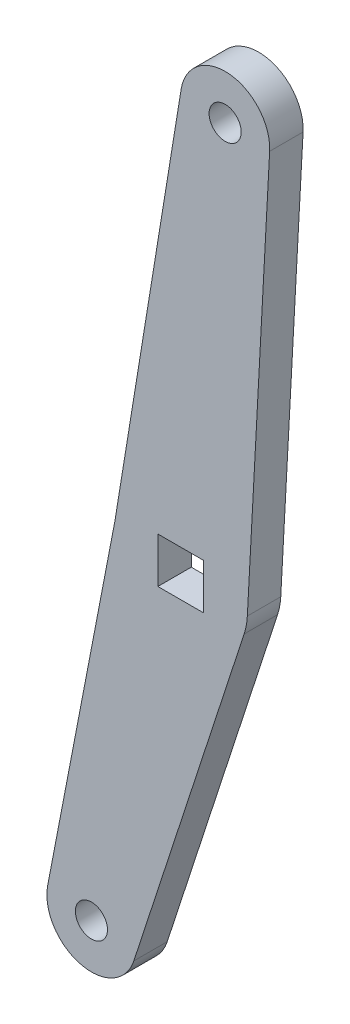
SolidWorks part; units mm, degrees
ref_plane "Front Plane" through (0, 0, 0) normal (0, 0, 1) x (1, 0, 0)
ref_plane "Top Plane" through (0, 0, 0) normal (0, 1, 0) x (1, 0, 0)
ref_plane "Right Plane" through (0, 0, 0) normal (1, 0, 0) x (0, 0, -1)
sketch "Sketch1" plane through (0, 0, 0) normal (0, 0, 1) x (1, 0, 0)
  line L0 (-6.2355, 1.2002) -> (3.3306, 50.8999)
  line L1 (0, 0) -> (29.7258, 0) construction
  line L2 (6.0371, -1.9687) -> (21.7557, 46.2339)
  line L3 (3.3626, 51.0802) -> (12.7824, 108.9699)
  line L4 (22.2112, 48.6737) -> (25.3908, 107.6079)
  line L7 (21.7557, 46.2339) -> (22.2112, 48.6737) construction
  line L8 (-2.905, 52.1001) -> (22.0632, 47.4389) construction
  line L10 (9.4615, 45.9484) -> (15.9385, 45.9484)
  line L11 (9.4615, 45.9484) -> (9.4615, 52.4254)
  line L12 (9.4615, 52.4254) -> (15.9385, 52.4254)
  line L13 (15.9385, 45.9484) -> (15.9385, 52.4254)
  line L14 (9.4615, 45.9484) -> (15.9385, 52.4254) construction
  line L15 (9.4615, 52.4254) -> (15.9385, 45.9484) construction
  circle A0 centre (0, 0) radius 2.286
  arc A1 (-6.2355, 1.2002) -> (6.0371, -1.9687) centre (0, 0) ccw
  circle A2 centre (19.05, 107.95) radius 2.286
  arc A4 (25.3908, 107.6079) -> (12.7824, 108.9699) centre (19.05, 107.95) ccw
  arc A8 (21.7557, 46.2339) -> (22.2112, 48.6737) centre (12.7, 49.1869) ccw
  arc A9 (3.3306, 50.8999) -> (3.3626, 51.0802) centre (-2.905, 52.1001) ccw
  circle A11 centre (19.05, 107.95) radius 2.286 construction
  arc A12 (12.7, 47.9369) -> (12.7, 50.4369) centre (12.7, 49.1869) ccw construction
  point P17 (3.3472, 50.99)
  point P21 (19.652, 107.4402)
  point P25 (0, 0)
  point P26 (12.966, 48.5255)
  dimension "D1" = 12.7
  dimension "D2" = 4.572
  dimension "D5" = 6.477
  dimension "D8" = 12.7
  dimension "D9" = 9.525
  dimension "D10" = 6.35
  dimension "D11" = 6.477
  dimension "D12" = 9.525
extrude "Boss-Extrude1" add sketch "Sketch1" along normal blind 4.7625
